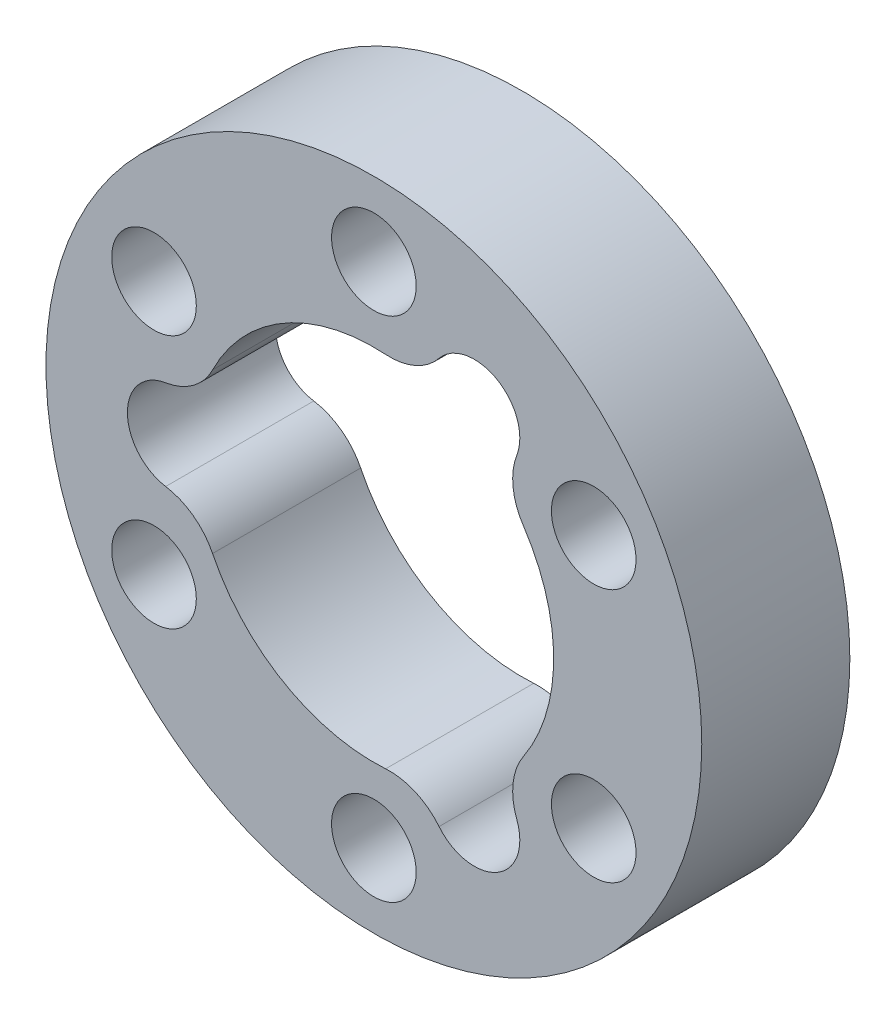
SolidWorks part; units mm, degrees
ref_plane "前视基准面" through (0, 0, 0) normal (0, 0, 1) x (1, 0, 0)
ref_plane "上视基准面" through (0, 0, 0) normal (0, 1, 0) x (1, 0, 0)
ref_plane "右视基准面" through (0, 0, 0) normal (1, 0, 0) x (0, 0, -1)
other "Configuration Table"
sketch "草图1" plane through (0, 0, 0) normal (0, 0, 1) x (1, 0, 0)
  line L0 (0, 12) -> (0, 0) construction
  line L1 (0, 0) -> (4.75, 8.2272) construction
  circle A0 centre (0, 12) radius 2
  circle A1 centre (10.3923, 6) radius 2
  circle A2 centre (10.3923, -6) radius 2
  circle A3 centre (0, -12) radius 2
  circle A4 centre (-10.3923, -6) radius 2
  circle A5 centre (-10.3923, 6) radius 2
  circle A6 centre (4.75, 8.2272) radius 2.15
  circle A7 centre (4.75, -8.2272) radius 2.15
  circle A8 centre (-9.5, 0) radius 2.15
  circle A9 centre (0, 0) radius 15.5
  circle A10 centre (0, 0) radius 8.5
  point P15 (0, 0)
  point P23 (0, 0)
  dimension "D1" = 4
  dimension "D4" = 4.3
  dimension "D8" = 31
  dimension "D9" = 17
  dimension "D2" = 12
  dimension "D5" = 30
  dimension "D6" = 9.5
  dimension "D3" = 6
  dimension "D7" = 3
extrude "凸台-拉伸1" add sketch "草图1" along normal blind 7 contours A9 A10 A6 A7 A8 A0 A1 A2 A3 A4 A5
fillet "圆角1" radius 3 6 edges at (-8.3093, 1.7902, 3.5) (-8.3093, -1.7902, 3.5) (2.6043, -8.0912, 3.5) (5.705, -6.301, 3.5) (5.705, 6.301, 3.5) (2.6043, 8.0912, 3.5)
